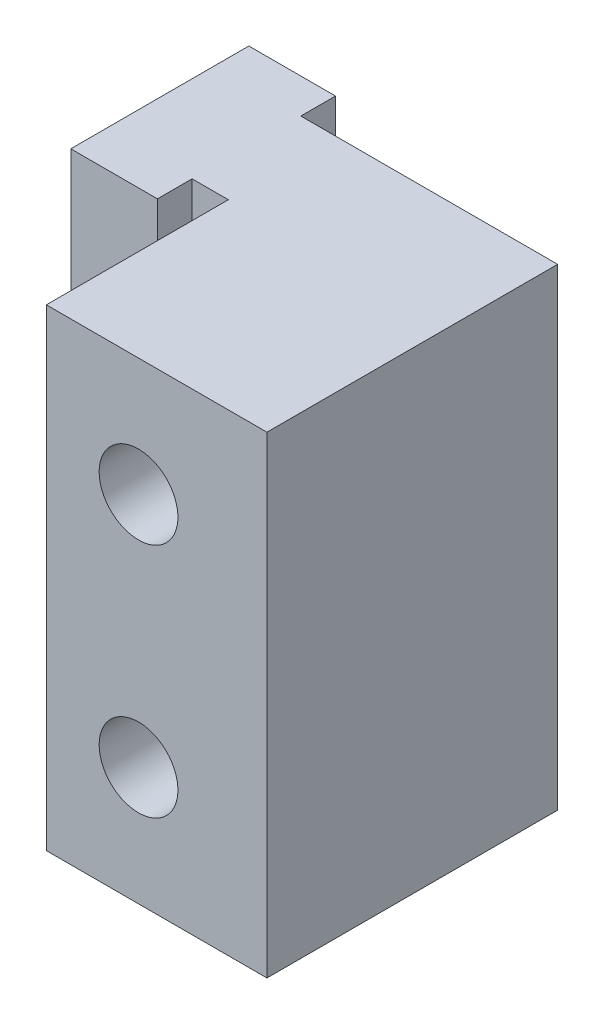
SolidWorks part; units mm, degrees
ref_plane "Front" through (0, 0, 0) normal (0, 0, 1) x (1, 0, 0)
ref_plane "Top" through (0, 0, 0) normal (0, 1, 0) x (1, 0, 0)
ref_plane "Right" through (0, 0, 0) normal (1, 0, 0) x (0, 0, -1)
sketch "Sketch1" plane through (0, 0, 0) normal (0, 1, 0) x (1, 0, 0)
  line L0 (2.75, 2.825) -> (3.9, 2.825)
  line L1 (0, 0) -> (2.75, 0)
  line L2 (0, 0) -> (0, 5.65)
  line L3 (0, 5.65) -> (2.75, 5.65)
  line L4 (2.75, 0) -> (2.75, 5.65)
  line L5 (3.9, 2.825) -> (3.9, 4.55)
  line L7 (3.9, 4.55) -> (2.75, 4.55)
  line L8 (3.9, 1.1) -> (2.75, 1.1)
  line L9 (3.9, 2.825) -> (3.9, -4.675)
  line L10 (3.9, -4.675) -> (10.9, -4.675)
  line L11 (10.9, -4.675) -> (10.9, 4.55)
  line L12 (10.9, 4.55) -> (3.9, 4.55)
  dimension "D1" = 5.65
  dimension "D2" = 2.75
  dimension "D3" = 1.725
  dimension "D4" = 1.725
  dimension "D5" = 1.15
  dimension "D6" = 7.5
  dimension "D7" = 7
extrude "Boss-Extrude1" add sketch "Sketch1" along normal blind 15 contours L1 L4 L3 L2 | L5 L7 L4 L0 | L9 L0 L4 L8 | L11 L12 L5 L9 L10
sketch "Sketch2" plane through (0, 0, -4.55) normal (0, 0, -1) x (-1, 0, 0)
  line L0 (-6.825, 15) -> (-6.825, 7.5)
  line L6 (-10.9, 15) -> (-2.75, 15) construction
  line L7 (-6.825, 7.5) -> (-6.825, 0)
  line L8 (-10.9, 0) -> (-2.75, 0) construction
  circle A2 centre (-6.825, 11.25) radius 1.25
  circle A3 centre (-6.825, 3.75) radius 1.25
  dimension "D1" = 7.5
extrude "Cut-Extrude1" cut sketch "Sketch2" against normal through all
